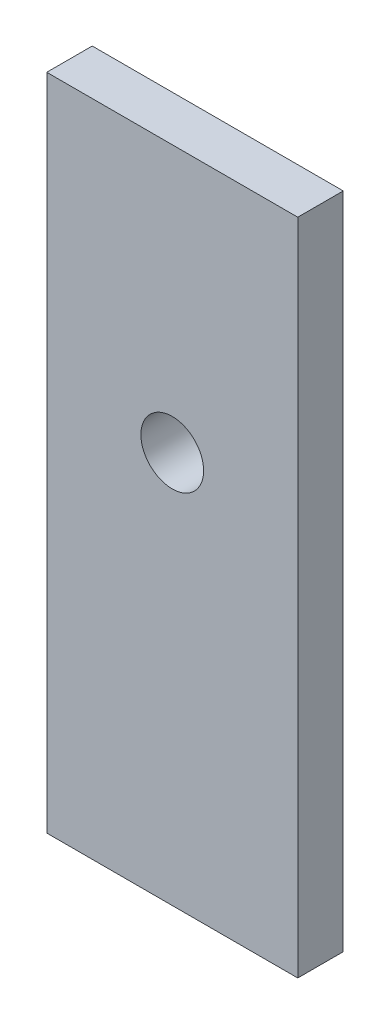
SolidWorks part; units mm, degrees
material "Бальса"
ref_plane "Спереди" through (0, 0, 0) normal (0, 0, 1) x (1, 0, 0)
ref_plane "Сверху" through (0, 0, 0) normal (0, 1, 0) x (1, 0, 0)
ref_plane "Справа" through (0, 0, 0) normal (1, 0, 0) x (0, 0, -1)
sketch "Эскиз1" plane through (0, 0, 0) normal (0, 0, 1) x (1, 0, 0)
  line L0 (16, 84) -> (16, 0) construction
  line L1 (0, 0) -> (32, 0)
  line L2 (0, 0) -> (0, 84)
  line L3 (0, 84) -> (32, 84)
  line L4 (32, 0) -> (32, 84)
  line L5 (16, 42) -> (32, 42) construction
  circle A0 centre (16, 50) radius 4
  dimension "D3" = 8
  dimension "D1" = 84
  dimension "D2" = 32
  dimension "D4" = 8
extrude "Бобышка-Вытянуть1" add sketch "Эскиз1" along normal blind 5.8
